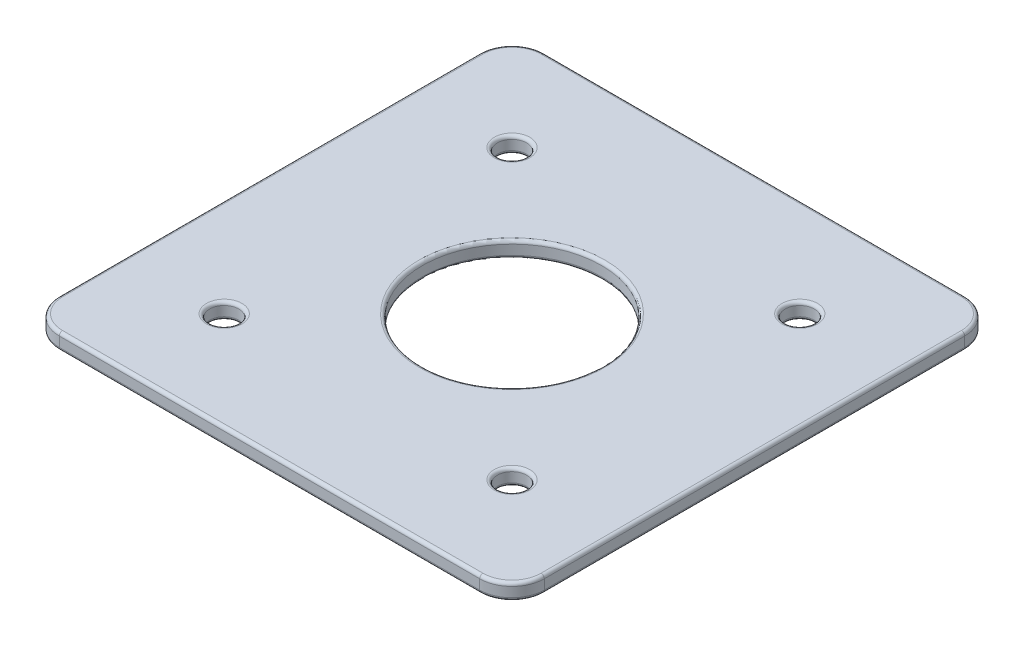
SolidWorks part; units mm, degrees
ref_plane "Front Plane" through (0, 0, 0) normal (0, 0, 1) x (1, 0, 0)
ref_plane "Top Plane" through (0, 0, 0) normal (0, 1, 0) x (1, 0, 0)
ref_plane "Right Plane" through (0, 0, 0) normal (1, 0, 0) x (0, 0, -1)
sketch "Sketch1" plane through (0, 0, 0) normal (0, 1, 0) x (1, 0, 0)
  line L1 (-75, -75) -> (75, -75)
  line L2 (-75, -75) -> (-75, 75)
  line L3 (-75, 75) -> (75, 75)
  line L4 (75, -75) -> (75, 75)
  line L5 (-75, -75) -> (75, 75) construction
  line L6 (-75, 75) -> (75, -75) construction
  circle A0 centre (0, 0) radius 27.75
  point P0 (0, 0)
  dimension "D3" = 55.5
  dimension "D1" = 150
  dimension "D2" = 150
extrude "Boss-Extrude1" add sketch "Sketch1" against normal blind 5
sketch "Sketch2" plane through (0, 0, 0) normal (0, 1, 0) x (1, 0, 0)
  line L1 (0, 75) -> (0, -75) construction
  line L2 (75, 75) -> (-75, 75) construction
  line L3 (-75, -75) -> (75, -75) construction
  line L4 (-75, 0) -> (75, 0) construction
  line L5 (-75, 75) -> (-75, -75) construction
  line L6 (75, -75) -> (75, 75) construction
  line L7 (0, 0) -> (75, 75) construction
  circle A4 centre (44.4982, 44.4982) radius 4.5
  circle A5 centre (-44.4982, 44.4982) radius 4.5
  circle A6 centre (44.4982, -44.4982) radius 4.5
  circle A7 centre (-44.4982, -44.4982) radius 4.5
  dimension "D3" = 9
  dimension "D2" = 62.93
extrude "Cut-Extrude1" cut sketch "Sketch2" against normal blind 5
fillet "Fillet1" radius 10 4 edges at (-75, -2.5, -75) (75, -2.5, -75) (75, -2.5, 75) (-75, -2.5, 75)
fillet "Fillet2" radius 1 26 edges at (-72.0711, -5, 72.0711) (0, -5, 75) (72.0711, -5, 72.0711) (75, -5, 0) (72.0711, -5, -72.0711) (0, -5, -75) (-72.0711, -5, -72.0711) (-75, -5, 0) (0, -5, 27.75) (72.0711, 0, -72.0711) (75, 0, 0) (72.0711, 0, 72.0711) (0, 0, 75) (-72.0711, 0, 72.0711) (-75, 0, 0) (-72.0711, 0, -72.0711) (0, 0, -75) (0, 0, 27.75) (44.4982, -5, -39.9982) (44.4982, 0, -39.9982) (-44.4982, -5, 48.9982) (44.4982, -5, 39.9982) (-44.4982, -5, -48.9982) (-44.4982, 0, 48.9982) (44.4982, 0, 39.9982) (-44.4982, 0, -48.9982)
